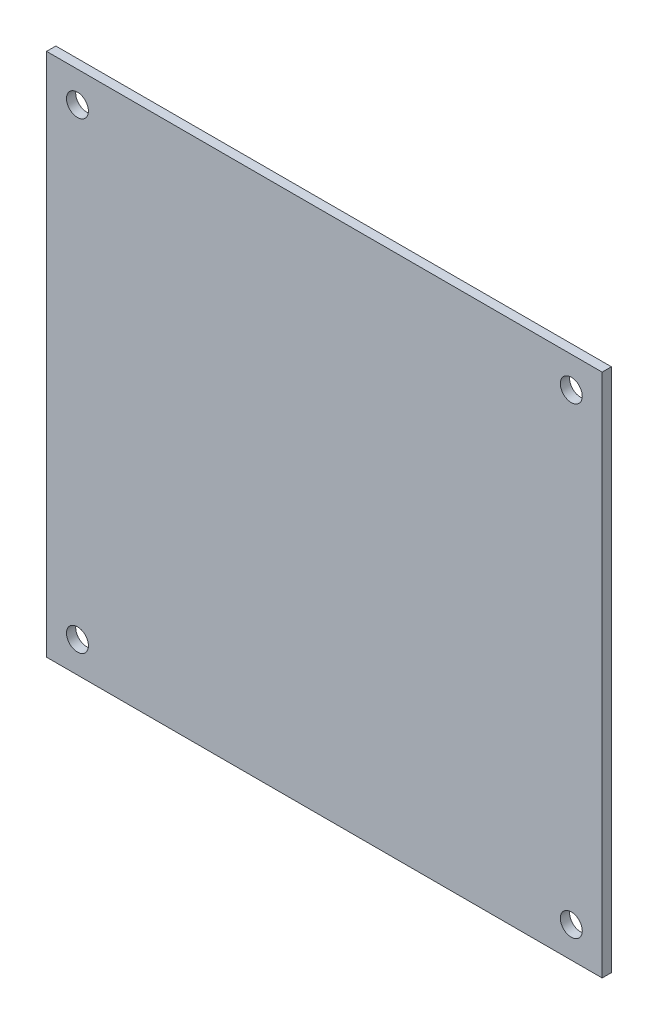
SolidWorks part; units mm, degrees
ref_plane "Front Plane" through (0, 0, 0) normal (0, 0, 1) x (1, 0, 0)
ref_plane "Top Plane" through (0, 0, 0) normal (0, 1, 0) x (1, 0, 0)
ref_plane "Right Plane" through (0, 0, 0) normal (1, 0, 0) x (0, 0, -1)
sketch "Sketch1" plane through (0, 0, 0) normal (0, 0, 1) x (1, 0, 0)
  line L1 (-45, 42.5) -> (45, 42.5)
  line L2 (-45, 42.5) -> (-45, -42.5)
  line L3 (-45, -42.5) -> (45, -42.5)
  line L4 (45, 42.5) -> (45, -42.5)
  line L5 (-45, 42.5) -> (45, -42.5) construction
  line L6 (-45, -42.5) -> (45, 42.5) construction
  circle A0 centre (-40, 37.5) radius 1.778
  circle A1 centre (-40, -37.5) radius 1.778
  circle A2 centre (40, 37.5) radius 1.778
  circle A3 centre (40, -37.5) radius 1.778
  point P0 (0, 0)
  dimension "D3" = 3.556
  dimension "D1" = 90
  dimension "D2" = 85
  dimension "D4" = 5
  dimension "D5" = 5
  dimension "D6" = 5
  dimension "D7" = 5
extrude "Boss-Extrude1" add sketch "Sketch1" along normal blind 1.5
